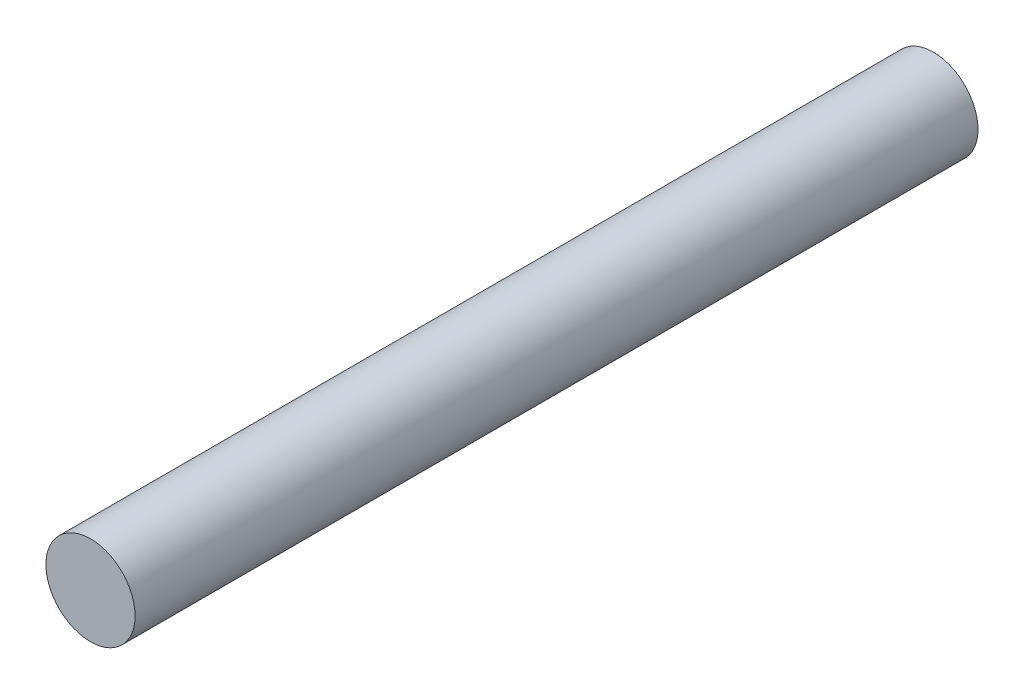
SolidWorks part; units mm, degrees
ref_plane "Front" through (0, 0, 0) normal (0, 0, 1) x (1, 0, 0)
ref_plane "Top" through (0, 0, 0) normal (0, 1, 0) x (1, 0, 0)
ref_plane "Right" through (0, 0, 0) normal (1, 0, 0) x (0, 0, -1)
sketch "Sketch1" plane through (0, 0, 0) normal (0, 0, 1) x (1, 0, 0)
  circle A0 centre (0, 0) radius 3.175
  dimension "D1" = 6.35
extrude "Boss-Extrude1" add sketch "Sketch1" along normal blind 60
